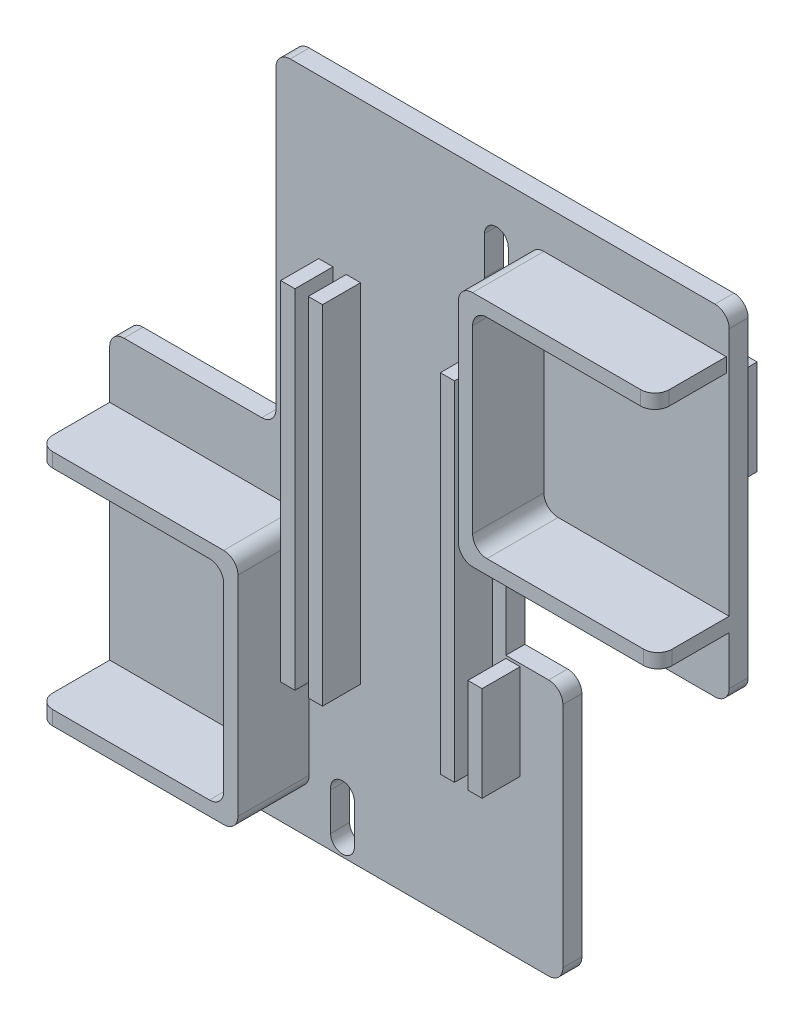
SolidWorks part; units mm, degrees
ref_plane "Front Plane" through (0, 0, 0) normal (0, 0, 1) x (1, 0, 0)
ref_plane "Top Plane" through (0, 0, 0) normal (0, 1, 0) x (1, 0, 0)
ref_plane "Right Plane" through (0, 0, 0) normal (1, 0, 0) x (0, 0, -1)
sketch "Sketch3" plane through (0, 0, 0) normal (0, 0, 1) x (1, 0, 0)
  line L0 (-6.95, 0) -> (6.95, 0) construction
  line L2 (-7.7, 18.3) -> (-6.2, 18.3)
  line L3 (-7.7, 18.3) -> (-7.7, -18.3)
  line L4 (-7.7, -18.3) -> (-6.2, -18.3)
  line L5 (-6.2, 18.3) -> (-6.2, -18.3)
  line L6 (-7.7, 18.3) -> (-6.2, -18.3) construction
  line L7 (-7.7, -18.3) -> (-6.2, 18.3) construction
  line L8 (-10.6, 18.3) -> (-9.1, 18.3)
  line L9 (-10.6, 18.3) -> (-10.6, -18.3)
  line L10 (-10.6, -18.3) -> (-9.1, -18.3)
  line L11 (-9.1, 18.3) -> (-9.1, -18.3)
  line L12 (-10.6, 18.3) -> (-9.1, -18.3) construction
  line L13 (-10.6, -18.3) -> (-9.1, 18.3) construction
  line L14 (6.2, 18.3) -> (7.7, 18.3)
  line L15 (6.2, 18.3) -> (6.2, -18.3)
  line L16 (6.2, -18.3) -> (7.7, -18.3)
  line L17 (7.7, 18.3) -> (7.7, -18.3)
  line L18 (6.2, 18.3) -> (7.7, -18.3) construction
  line L19 (6.2, -18.3) -> (7.7, 18.3) construction
  line L20 (10.6, 18.3) -> (9.1, 18.3)
  line L21 (10.6, 18.3) -> (10.6, -18.3)
  line L22 (10.6, -18.3) -> (9.1, -18.3)
  line L23 (9.1, 18.3) -> (9.1, -18.3)
  line L24 (10.6, 18.3) -> (9.1, -18.3) construction
  line L25 (10.6, -18.3) -> (9.1, 18.3) construction
  point P3 (-9.85, 0)
  point P16 (9.85, 0)
  dimension "D1" = 6.95
  dimension "D2" = 6.95
  dimension "D3" = 36.6
  dimension "D4" = 36.6
  dimension "D5" = 36.6
  dimension "D6" = 36.6
  dimension "D7" = 0
  dimension "D8" = 0
  dimension "D9" = 1.5
  dimension "D10" = 1.5
  dimension "D11" = 1.4
  dimension "D12" = 1.5
  dimension "D13" = 1.4
  dimension "D14" = 1.5
extrude "Boss-Extrude1" add sketch "Sketch3" along normal blind 4
sketch "Sketch4" plane through (0, 0, 0) normal (0, 0, 1) x (1, 0, 0)
  line L1 (-32.6, 35) -> (32.6, 35)
  line L2 (-32.6, 35) -> (-32.6, -35)
  line L3 (-32.6, -35) -> (32.6, -35)
  line L4 (32.6, 35) -> (32.6, -35)
  line L5 (-32.6, 35) -> (32.6, -35) construction
  line L6 (-32.6, -35) -> (32.6, 35) construction
  point P0 (0, 0)
  dimension "D1" = 70
  dimension "D2" = 65.2
extrude "Boss-Extrude2" add sketch "Sketch4" against normal blind 2
sketch "Sketch5" plane through (0, 0, 0) normal (0, 0, 1) x (1, 0, 0)
  line L0 (11.6, 30.8) -> (11.6, 5.8)
  line L1 (11.6, 5.8) -> (32.6, 5.8)
  line L2 (32.6, 5.8) -> (32.6, 7.3)
  line L3 (32.6, 7.3) -> (13.1, 7.3)
  line L4 (13.1, 7.3) -> (13.1, 29.3)
  line L5 (13.1, 29.3) -> (32.2947, 29.3)
  line L6 (32.2947, 29.3) -> (32.2947, 30.8)
  line L7 (32.2947, 30.8) -> (11.6, 30.8)
  line L8 (-32.6, -5.8) -> (-11.6, -5.8)
  line L9 (-11.6, -5.8) -> (-11.6, -30.8)
  line L10 (-11.6, -30.8) -> (-32.6, -30.8)
  line L11 (-32.6, -30.8) -> (-32.6, -29.3)
  line L12 (-32.6, -29.3) -> (-13.1, -29.3)
  line L13 (-13.1, -29.3) -> (-13.1, -7.3)
  line L14 (-13.1, -7.3) -> (-32.6, -7.3)
  line L15 (-32.6, -5.8) -> (-32.6, -7.3)
  line L16 (10.6, -18.3) -> (10.6, 18.3) construction
  line L17 (-7.7, -18.3) -> (-6.2, -18.3) construction
  line L18 (10.6, 18.3) -> (9.1, 18.3) construction
  line L19 (-10.6, 18.3) -> (-10.6, -18.3) construction
  dimension "D1" = 21
  dimension "D2" = 19.5
  dimension "D3" = 22
  dimension "D4" = 25
  dimension "D5" = 1.5
  dimension "D6" = 1
  dimension "D7" = 21
  dimension "D8" = 19.5
  dimension "D9" = 22
  dimension "D10" = 25
  dimension "D11" = 1.5
  dimension "D12" = 11
  dimension "D13" = 11
  dimension "D14" = 1
  dimension "D15" = 21
extrude "Boss-Extrude3" add sketch "Sketch5" along normal blind 7.5
sketch "Sketch6" plane through (0, 0, 0) normal (0, 0, 1) x (1, 0, 0)
  line L0 (-32.6, 35) -> (-32.6, -5.8) construction
  line L1 (-32.6, 30) -> (-15.1, 30)
  line L2 (-32.6, 30) -> (-32.6, 0.8)
  line L3 (-32.6, 0.8) -> (-15.1, 0.8)
  line L4 (-15.1, 30) -> (-15.1, 0.8)
  line L5 (32.6, -35) -> (32.6, 5.8) construction
  line L6 (32.6, -0.8) -> (15.1, -0.8)
  line L7 (32.6, -0.8) -> (32.6, -30)
  line L8 (32.6, -30) -> (15.1, -30)
  line L9 (15.1, -0.8) -> (15.1, -30)
  line L10 (-32.6, -35) -> (32.6, -35) construction
other "AlignGroup1" parameters "D1"=19.5486, "D2"=19.4425, "D3"=5, "D4"=4.2814, "D5"=26.6576, "D6"=24.8537
extrude "Cut-Extrude1" cut sketch "Sketch6" against normal blind 4
sketch "Sketch10" plane through (0, 0, -2) normal (0, 0, -1) x (-1, 0, 0)
  line L0 (-13.1, 7.3) -> (-13.1, 29.3) construction
  line L1 (-13.1, 29.3) -> (-32.2947, 29.3) construction
  line L3 (13.1, -29.3) -> (32.6, -29.3) construction
  line L4 (13.1, -7.3) -> (13.1, -29.3) construction
  circle A0 centre (-15.1, 27.3) radius 1.5
  circle A1 centre (15.1, -27.3) radius 1.5
  dimension "D1" = 3
  dimension "D2" = 3
  dimension "D3" = 2
  dimension "D4" = 2
  dimension "D5" = 2
  dimension "D6" = 2
extrude "Cut-Extrude5" cut sketch "Sketch10" against normal blind 20
sketch "Sketch11" plane through (0, 0, 0) normal (0, 0, 1) x (1, 0, 0)
  line L0 (-15.1, 0.8) -> (-15.1, 30) construction
  line L1 (-15.1, 25.8376) -> (-38.7298, 25.8376)
  line L2 (-15.1, 25.8376) -> (-15.1, 39.6317)
  line L3 (-15.1, 39.6317) -> (-38.7298, 39.6317)
  line L4 (-38.7298, 25.8376) -> (-38.7298, 39.6317)
  line L5 (15.1, -0.8) -> (15.1, -30) construction
  line L6 (15.1, -25.5192) -> (34.5916, -25.5192)
  line L7 (15.1, -25.5192) -> (15.1, -38.2523)
  line L8 (15.1, -38.2523) -> (34.5916, -38.2523)
  line L9 (34.5916, -25.5192) -> (34.5916, -38.2523)
  line L10 (-32.6, -30.8) -> (-11.6, -30.8) construction
  line L11 (-32.6, -35) -> (32.6, -35) construction
  line L12 (32.6, 35) -> (-32.6, 35) construction
  line L13 (32.2947, 30.8) -> (11.6, 30.8) construction
  dimension "D1" = 4.2
  dimension "D2" = 4.2
extrude "Cut-Extrude6" cut sketch "Sketch11" against normal blind 20
sketch "Sketch13" plane through (10.6, 0, 0) normal (1, 0, 0) x (0, 0, -1)
  line L0 (-4, -18.3) -> (-4, 18.3) construction
  line L1 (-4, -8.3) -> (0, -8.3)
  line L2 (-4, -8.3) -> (-4, 8.3)
  line L3 (-4, 8.3) -> (0, 8.3)
  line L4 (0, -8.3) -> (0, 8.3)
  line L5 (0, -0.8) -> (0, 5.8) construction
  line L6 (-4, -18.3) -> (0, -18.3) construction
  line L7 (-4, 18.3) -> (0, 18.3) construction
  dimension "D1" = 10
  dimension "D2" = 10
extrude "Cut-Extrude7" cut sketch "Sketch13" against normal blind 2
sketch "Sketch15" plane through (0, 0, 0) normal (0, 0, 1) x (1, 0, 0)
  line L0 (9.1, 10.1814) -> (9.1, -10.3863) construction
  line L1 (9.1, 18.3) -> (9.1, 8.3) construction
  line L2 (9.1, -8.3) -> (9.1, -18.3) construction
  line L4 (9.1, 5.8) -> (15.1, 5.8)
  line L5 (9.1, 5.8) -> (9.1, -5.8)
  line L6 (9.1, -5.8) -> (15.1, -5.8)
  line L7 (15.1, 5.8) -> (15.1, -5.8)
  line L8 (10.6, -8.3) -> (9.1, -8.3) construction
  line L9 (11.6, 5.8) -> (32.6, 5.8) construction
  line L10 (15.1, -0.8) -> (15.1, -35) construction
  dimension "D1" = 0
  dimension "D2" = 2.5
  dimension "D3" = 0
extrude "Cut-Extrude8" cut sketch "Sketch15" against normal blind 2
sketch "Sketch16" plane through (0, 0, 0) normal (0, 0, 1) x (1, 0, 0)
  line L2 (-13.1, -29.3) -> (-32.6, -29.3) construction
  line L3 (-6.85, -29.3) -> (-6.85, -33.4806)
  line L5 (-9.35, -33.4806) -> (-9.3369, -29.4806)
  line L7 (-11.6, -30.8) -> (-11.6, -5.8) construction
  line L8 (11.6, 29.3) -> (8.1, 29.3) construction
  line L9 (11.6, 30.8) -> (11.6, 5.8) construction
  line L10 (6.85, 29.3) -> (6.85, 25.3)
  line L11 (13.1, 29.3) -> (32.2947, 29.3) construction
  line L12 (9.35, 25.3) -> (9.35, 29.3)
  arc A0 (-6.85, -29.3) -> (-9.3369, -29.4806) centre (-8.1, -29.3) ccw
  arc A1 (-9.35, -33.4806) -> (-6.85, -33.4806) centre (-8.1, -33.4806) ccw
  arc A2 (9.35, 29.3) -> (6.85, 29.3) centre (8.1, 29.3) ccw
  arc A3 (6.85, 25.3) -> (9.35, 25.3) centre (8.1, 25.3) ccw
  dimension "D1" = 2.5
  dimension "D2" = 2.5
  dimension "D7" = 2.5
  dimension "D8" = 2.5
  dimension "D3" = 0
  dimension "D4" = 4
  dimension "D5" = 3.5
  dimension "D6" = 3.5
  dimension "D9" = 4
  dimension "D10" = 0
extrude "Cut-Extrude9" cut sketch "Sketch16" against normal blind 2
fillet "Fillet1" radius 1.5 22 edges at (32.6, 35, -1) (15.1, -35, -1) (13.1, 7.3, 3.75) (13.1, 29.3, 3.75) (32.2947, 30.05, 7.5) (32.6, 6.55, 7.5) (32.6, -0.8, -1) (15.1, -0.8, -1) (15.1, 5.8, -1) (15.1, -5.8, -1) (-32.6, -6.55, 7.5) (-32.6, -30.05, 7.5) (-13.1, -29.3, 3.75) (-13.1, -7.3, 3.75) (-32.6, -35, -1) (-32.6, 0.8, -1) (-15.1, 0.8, -1) (-15.1, 35, -1) (11.6, 5.8, 3.75) (11.6, 30.8, 3.75) (-11.6, -30.8, 3.75) (-11.6, -5.8, 3.75)
sketch "Sketch18" plane through (0, 0, 0) normal (0, 0, 1) x (1, 0, 0)
  line L0 (11.6, 29.3) -> (11.6, 7.3) construction
  line L1 (9.1, 8.3) -> (11.6, 8.3)
  line L2 (9.1, 8.3) -> (9.1, -8.0112)
  line L4 (11.6, 8.3) -> (11.6, -5.8)
  line L5 (11.6, -5.8) -> (16.4955, -5.8)
  line L7 (16.4955, -5.8) -> (16.4955, -8.0112)
  line L8 (9.1, -8.0112) -> (16.4955, -8.0112)
  dimension "D1" = 0
extrude "Cut-Extrude11" cut sketch "Sketch18" against normal blind 2
fillet "Fillet2" radius 1.5 2 edges at (11.6, 5.8, -1) (15.1, -8.0112, -1)
sketch "Sketch19" plane through (0, 0, -2) normal (0, 0, -1) x (-1, 0, 0)
  line L0 (-31.1, 35) -> (13.6, 35) construction
  line L1 (-32.6, 0.7) -> (-32.6, 33.5) construction
  line L2 (31.1, -35) -> (-13.6, -35) construction
  line L3 (32.6, -0.7) -> (32.6, -33.5) construction
  line L5 (-18.6, 25) -> (-28.6, 25)
  line L6 (-18.6, 25) -> (-18.6, 15)
  line L7 (-18.6, 15) -> (-28.6, 15)
  line L8 (-28.6, 25) -> (-28.6, 15)
  line L9 (-18.6, 25) -> (-28.6, 15) construction
  line L10 (-18.6, 15) -> (-28.6, 25) construction
  line L11 (28.6, -15) -> (18.6, -15)
  line L12 (28.6, -15) -> (28.6, -25)
  line L13 (28.6, -25) -> (18.6, -25)
  line L14 (18.6, -15) -> (18.6, -25)
  line L15 (28.6, -15) -> (18.6, -25) construction
  line L16 (28.6, -25) -> (18.6, -15) construction
  point P8 (-23.6, 20)
  point P13 (23.6, -20)
  dimension "D1" = 4
  dimension "D2" = 4
  dimension "D3" = 10
  dimension "D4" = 10
  dimension "D5" = 10
  dimension "D6" = 10
  dimension "D7" = 15
  dimension "D8" = 15
extrude "Boss-Extrude5" add sketch "Sketch19" along normal blind 4.95
